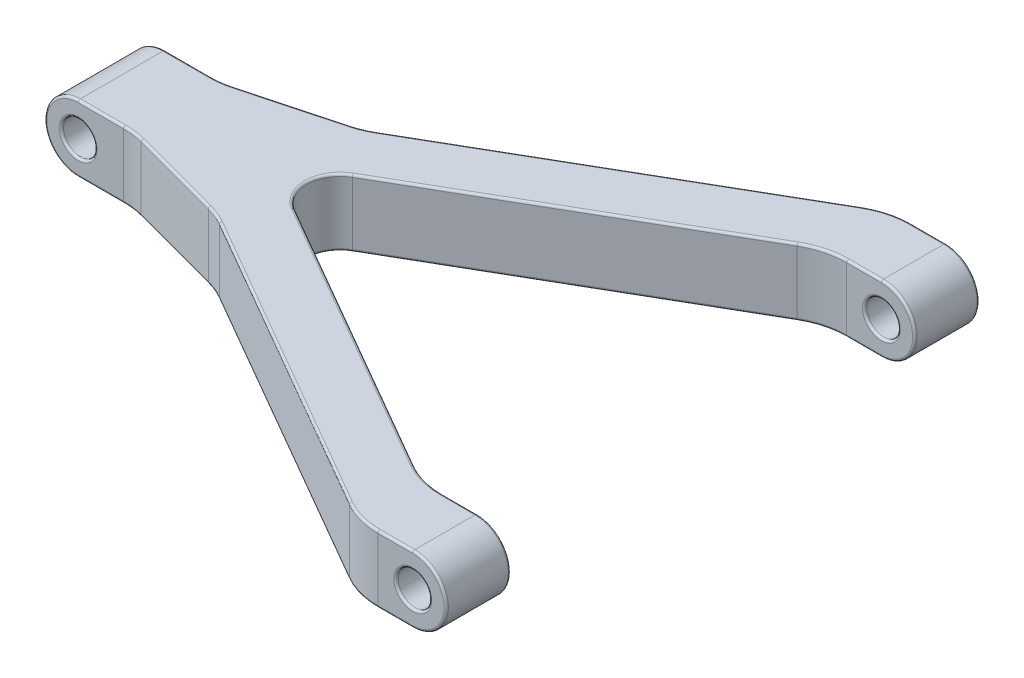
SolidWorks part; units mm, degrees
ref_plane "Front Plane" through (0, 0, 0) normal (0, 0, 1) x (1, 0, 0)
ref_plane "Top Plane" through (0, 0, 0) normal (0, 1, 0) x (1, 0, 0)
ref_plane "Right Plane" through (0, 0, 0) normal (1, 0, 0) x (0, 0, -1)
sketch "Sketch1" plane through (0, 0, 0) normal (0, 1, 0) x (1, 0, 0)
  line L0 (0, 0) -> (336.4065, 0) construction
  line L1 (-193.529, -39) -> (-193.529, 39)
  line L2 (-193.529, 39) -> (-143.529, 39)
  line L3 (-143.529, 39) -> (-43.529, 65.7949)
  line L4 (-43.529, 65.7949) -> (256.471, 239)
  line L5 (256.471, 239) -> (306.471, 239)
  line L6 (256.471, -239) -> (306.471, -239)
  line L7 (-43.529, -65.7949) -> (256.471, -239)
  line L8 (-143.529, -39) -> (-43.529, -65.7949)
  line L9 (-193.529, -39) -> (-143.529, -39)
  line L10 (306.471, 239) -> (306.471, 181.26)
  line L11 (306.471, 181.26) -> (256.4624, 181.26)
  line L12 (256.4624, 181.26) -> (-12.4892, 25.9808)
  line L13 (-12.4892, -25.9808) -> (256.4624, -181.26)
  line L14 (256.4624, -181.26) -> (306.471, -181.26)
  line L15 (306.471, -181.26) -> (306.471, -239)
  arc A0 (-12.4892, 25.9808) -> (-12.4892, -25.9808) centre (2.5108, 0) ccw
  point P14 (-193.529, 0)
  dimension "D12" = 30
  dimension "D1" = 39
  dimension "D2" = 100
  dimension "D3" = 300
  dimension "D4" = 50
  dimension "D5" = 500
  dimension "D6" = 165
  dimension "D7" = 165
  dimension "D8" = 50
  dimension "D9" = 57.74
  dimension "D10" = 57.74
  dimension "D11" = 362.52
extrude "Boss-Extrude1" add sketch "Sketch1" along normal blind 60
sketch "Sketch2" plane through (0, 0, 39) normal (0, 0, 1) x (1, 0, 0)
  line L0 (-193.529, 60) -> (-193.529, 0) construction
  circle A0 centre (-193.529, 30) radius 30
extrude "Boss-Extrude2" add sketch "Sketch2" against normal up to surface (78 mm away) up to face at (-168.529, 30, -39)
sketch "Sketch3" plane through (0, 0, 39) normal (0, 0, 1) x (1, 0, 0)
  line L3 (-143.529, 60) -> (-193.529, 60)
  line L4 (-193.529, 0) -> (-143.529, 0)
  line L5 (-143.529, 0) -> (-143.529, 60)
  line L6 (-143.529, 60) -> (-193.529, 60)
  line L7 (-193.529, 0) -> (-143.529, 0)
  line L8 (-143.529, 0) -> (-143.529, 60)
  circle A0 centre (-193.529, 30) radius 15
  arc A1 (-193.529, 60) -> (-193.529, 0) centre (-193.529, 30) ccw
  arc A2 (-193.529, 60) -> (-193.529, 0) centre (-193.529, 30) ccw
  dimension "D2" = 30
  dimension "D1" = 0
extrude "Cut-Extrude1" cut sketch "Sketch3" against normal up to surface (78 mm away) contours A0 up to face at (-176.029, 30, -39)
sketch "Sketch4" plane through (0, 0, -239) normal (0, 0, -1) x (-1, 0, 0)
  line L0 (-306.471, 60) -> (-306.471, 0) construction
  circle A0 centre (-306.471, 30) radius 30
extrude "Boss-Extrude3" add sketch "Sketch4" against normal up to surface (57.74 mm away) up to face at (281.4667, 30, -181.26)
sketch "Sketch5" plane through (0, 0, 239) normal (0, 0, 1) x (1, 0, 0)
  line L0 (306.471, 60) -> (306.471, 0) construction
  circle A0 centre (306.471, 30) radius 30
extrude "Boss-Extrude4" add sketch "Sketch5" against normal up to surface (57.74 mm away) up to face at (281.4667, 30, 181.26)
sketch "Sketch7" plane through (0, 0, -239) normal (0, 0, -1) x (-1, 0, 0)
  line L3 (-256.471, 60) -> (-306.471, 60)
  line L4 (-306.471, 0) -> (-256.471, 0)
  line L5 (-256.471, 0) -> (-256.471, 60)
  line L6 (-256.471, 60) -> (-306.471, 60)
  line L7 (-306.471, 0) -> (-256.471, 0)
  line L8 (-256.471, 0) -> (-256.471, 60)
  circle A0 centre (-306.471, 30) radius 15
  arc A1 (-306.471, 60) -> (-306.471, 0) centre (-306.471, 30) ccw
  arc A2 (-306.471, 60) -> (-306.471, 0) centre (-306.471, 30) ccw
  dimension "D2" = 30
  dimension "D1" = 0
extrude "Cut-Extrude2" cut sketch "Sketch7" against normal through all both and the other way through all contours A0
fillet "Fillet1" radius 70 8 edges at (-143.529, 30, -39) (-143.529, 30, 39) (256.471, 30, 239) (-43.529, 30, 65.7949) (256.4624, 30, 181.26) (256.4624, 30, -181.26) (256.471, 30, -239) (-43.529, 30, -65.7949)
fillet "Fillet2" radius 2 54 edges at (336.471, 30, 181.26) (336.471, 30, 239) (290.8449, 60, 181.26) (257.1015, 60, 178.8748) (113.8648, 60, 98.9313) (-27.4892, 60, 0) (113.8648, 60, -98.9313) (257.1015, 60, -178.8748) (290.8449, 60, -181.26) (336.471, 30, -181.26) (336.471, 30, -239) (290.8492, 60, -239) (257.1101, 60, -236.6148) (102.3397, 60, -150.0123) (-43.7602, 60, -66.353) (-93.529, 60, -52.3975) (-143.6079, 60, -39.5989) (-173.1369, 60, -39) (-223.529, 30, -39) (-223.529, 30, 39) (-173.1369, 60, 39) (-143.6079, 60, 39.5989) (-93.529, 60, 52.3975) (-43.7602, 60, 66.353) (102.3397, 60, 150.0123) (257.1101, 60, 236.6148) (290.8492, 60, 239) (321.471, 30, 181.26) (291.471, 30, 239) (291.471, 30, -181.26) (321.471, 30, -239) (-178.529, 30, 39) (-178.529, 30, -39) (290.8449, 0, 181.26) (257.1015, 0, 178.8748) (113.8648, 0, 98.9313) (-27.4892, 0, 0) (113.8648, 0, -98.9313) (257.1015, 0, -178.8748) (290.8449, 0, -181.26) (290.8492, 0, -239) (257.1101, 0, -236.6148) (102.3397, 0, -150.0123) (-43.7602, 0, -66.353) (-93.529, 0, -52.3975) (-143.6079, 0, -39.5989) (-173.1369, 0, -39) (-173.1369, 0, 39) (-143.6079, 0, 39.5989) (-93.529, 0, 52.3975) (-43.7602, 0, 66.353) (102.3397, 0, 150.0123) (257.1101, 0, 236.6148) (290.8492, 0, 239)
